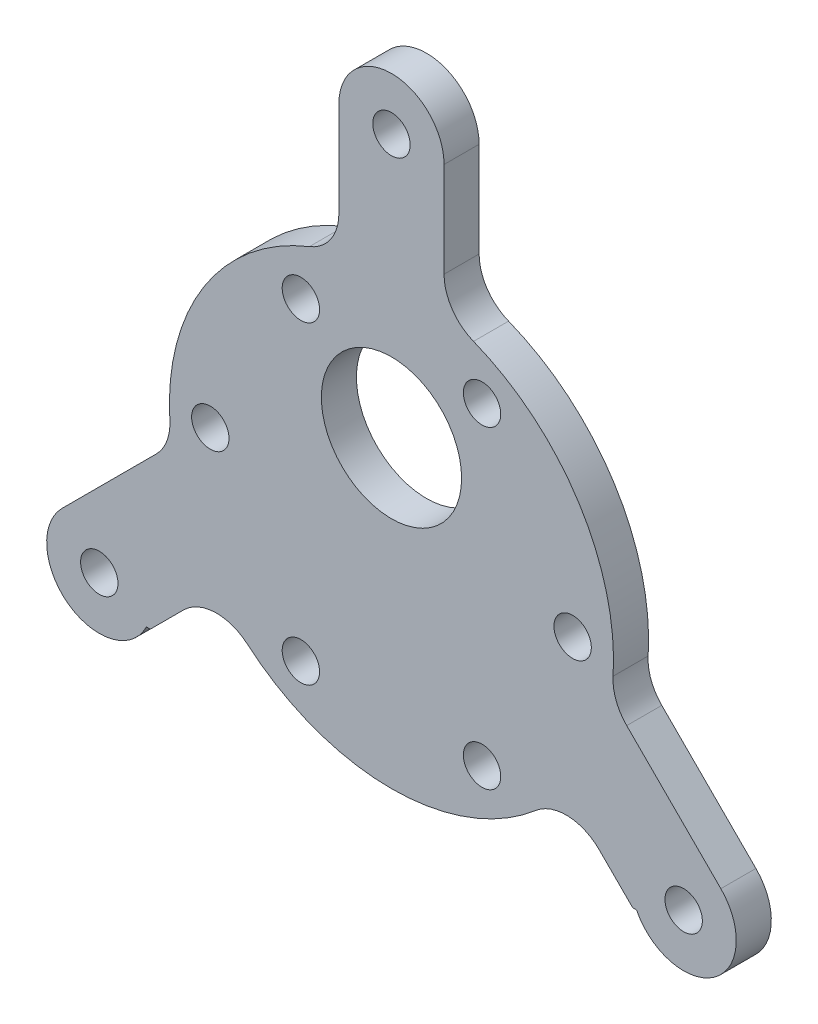
SolidWorks part; units mm, degrees
ref_plane "前视基准面" through (0, 0, 0) normal (0, 0, 1) x (1, 0, 0)
ref_plane "上视基准面" through (0, 0, 0) normal (0, 1, 0) x (1, 0, 0)
ref_plane "右视基准面" through (0, 0, 0) normal (1, 0, 0) x (0, 0, -1)
sketch "草图1" plane through (0, 0, 0) normal (0, 0, 1) x (1, 0, 0)
  line L0 (0, 32.5) -> (0, -32.5) construction
  line L1 (-80, 32.5) -> (80, 32.5)
  line L2 (-100, -32.5) -> (100, -32.5)
  line L3 (-80, 32.5) -> (-100, -32.5)
  line L4 (80, 32.5) -> (100, -32.5)
  line L5 (0, 22.5) -> (45, 22.5) construction
  line L6 (0, -22.5) -> (20, -22.5) construction
  line L7 (20, -22.5) -> (70, -22.5) construction
  line L8 (45, 22.5) -> (45, -22.5) construction
  line L9 (45, 0) -> (45, -7) construction
  line L10 (45, -7) -> (29.5, -7) construction
  line L11 (74.0914, 24.5) -> (89.1683, -24.5)
  line L12 (-89.1683, -24.5) -> (89.1683, -24.5)
  line L13 (-74.0914, 24.5) -> (-89.1683, -24.5)
  line L14 (-74.0914, 24.5) -> (74.0914, 24.5)
  line L15 (15.5, -22.5) -> (15.5, -24.5)
  line L16 (40.5, 22.5) -> (40.5, 24.5)
  line L17 (49.5, 22.5) -> (49.5, 24.5)
  line L18 (65.5, -22.5) -> (65.5, -24.5)
  line L19 (74.5, -22.5) -> (74.5, -24.5)
  line L20 (24.5, -22.5) -> (24.5, -24.5)
  line L21 (40.5, 22.5) -> (40.5, 11.4594)
  line L22 (49.5, 22.5) -> (49.5, 11.4594)
  line L23 (45, -7) -> (35.8948, -16.1052) construction
  line L24 (16.818, -19.318) -> (26.2244, -9.9116)
  line L25 (23.182, -25.682) -> (30.0888, -18.7752)
  line L28 (66.818, -25.682) -> (59.9112, -18.7752)
  line L29 (73.182, -19.318) -> (63.7756, -9.9116)
  circle A0 centre (45, 0) radius 6
  circle A1 centre (29.5, -7) radius 1.6
  circle A2 centre (37.25, 6.4234) radius 1.6
  circle A3 centre (52.75, 6.4234) radius 1.6
  circle A4 centre (60.5, -7) radius 1.6
  circle A5 centre (52.75, -20.4234) radius 1.6
  circle A6 centre (37.25, -20.4234) radius 1.6
  circle A7 centre (45, -7) radius 19
  circle A8 centre (20, -22.5) radius 1.6
  circle A9 centre (70, -22.5) radius 1.6
  circle A10 centre (45, 22.5) radius 1.6
  circle A12 centre (45, 22.5) radius 4.5
  circle A13 centre (20, -22.5) radius 4.5
  circle A14 centre (70, -22.5) radius 4.5
  point P3 (0, 0)
  point P8 (0, 32.5)
  point P11 (0, -32.5)
  point P33 (45, -7)
  point P62 (0, 0)
  point P63 (0, 0)
  dimension "D8" = 12
  dimension "D14" = 3.2
  dimension "D16" = 38
  dimension "D17" = 3.2
  dimension "D18" = 3.2
  dimension "D19" = 3.2
  dimension "D21" = 9
  dimension "D22" = 9
  dimension "D23" = 9
  dimension "D1" = 10
  dimension "D2" = 10
  dimension "D3" = 45
  dimension "D4" = 160
  dimension "D5" = 200
  dimension "D6" = 20
  dimension "D7" = 50
  dimension "D9" = 45
  dimension "D10" = 7
  dimension "D11" = 22.5
  dimension "D12" = 22.5
  dimension "D13" = 15.5
  dimension "D24" = 45
  dimension "D20" = 8
  dimension "D15" = 6
extrude "凸台-拉伸1" add sketch "草图1" along normal blind 3 contours A7 L12 A0 A1 A2 A3 A4 A5 A6 | A13 L20 L25 A7 L24 | A13 L12 A8 | L12 A13 | L12 A14 | A14 L29 A7 L28 L18 | A12 L21 A7 L22 | A12 L14 A10 | L14 A12 | A13 L12 L25 L20 | A14 L18 L28 L12 | A14 L12 A9 | L12 A7
fillet "圆角1" radius 4 6 edges at (63.7756, -9.9116, 1.5) (59.9112, -18.7752, 1.5) (30.0888, -18.7752, 1.5) (26.2244, -9.9116, 1.5) (49.5, 11.4594, 1.5) (40.5, 11.4594, 1.5)
